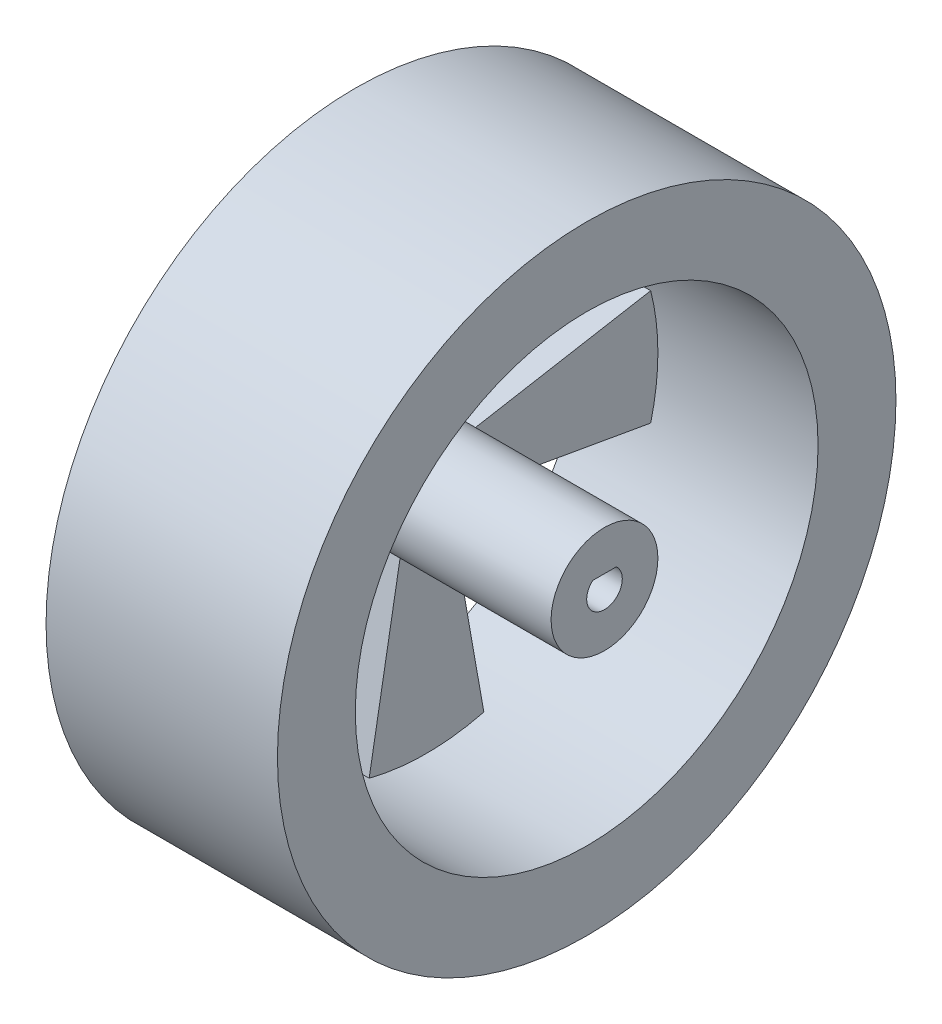
SolidWorks part; units mm, degrees
ref_plane "前视基准面" through (0, 0, 0) normal (0, 0, 1) x (1, 0, 0)
ref_plane "上视基准面" through (0, 0, 0) normal (0, 1, 0) x (1, 0, 0)
ref_plane "右视基准面" through (0, 0, 0) normal (1, 0, 0) x (0, 0, -1)
sketch "草图1" plane through (0, 0, 0) normal (1, 0, 0) x (0, 0, -1)
  circle A0 centre (0, 0) radius 34.75
  circle A1 centre (0, 0) radius 26
  dimension "D1" = 69.5
  dimension "D2" = 52
extrude "凸台-拉伸1" add sketch "草图1" along normal blind 26
ref_plane "基准面1" through (5, 0, 0) normal (1, 0, 0) x (0, 0, -1)
sketch "草图2" plane through (5, 0, 0) normal (1, 0, 0) x (0, 0, -1)
  line L1 (-2.4281, 2.4281) -> (-6.4416, 25.1894)
  line L2 (0, 2) -> (0, 13.4589) construction
  line L3 (2.4281, 2.4281) -> (6.4416, 25.1894)
  line L5 (2.4281, 2.4281) -> (25.1894, 6.4416)
  line L6 (2.4281, -2.4281) -> (25.1894, -6.4416)
  line L7 (2, 0) -> (13.4589, 0) construction
  line L9 (2.4281, -2.4281) -> (6.4416, -25.1894)
  line L10 (-2.4281, -2.4281) -> (-6.4416, -25.1894)
  line L13 (-2.4281, -2.4281) -> (-25.1894, -6.4416)
  line L14 (-2.4281, 2.4281) -> (-25.1894, 6.4416)
  line L16 (0, 0) -> (0, -2) construction
  line L17 (0, 0) -> (-2, 0) construction
  circle A0 centre (0, 0) radius 26 construction
  arc A1 (6.4416, 25.1894) -> (-6.4416, 25.1894) centre (0, 0) ccw
  arc A2 (25.1894, -6.4416) -> (25.1894, 6.4416) centre (0, 0) ccw
  arc A3 (-6.4416, -25.1894) -> (6.4416, -25.1894) centre (0, 0) ccw
  arc A4 (-25.1894, 6.4416) -> (-25.1894, -6.4416) centre (0, 0) ccw
  point P29 (0, 0)
  dimension "D3" = 4
extrude "凸台-拉伸2" add sketch "草图2" along normal blind 3 and the other way blind 3
sketch "草图3" plane through (8, 0, 0) normal (1, 0, 0) x (0, 0, -1)
  circle A0 centre (0, 0) radius 6
  dimension "D1" = 12
extrude "凸台-拉伸3" add sketch "草图3" along normal blind 20
sketch "草图4" plane through (28, 0, 0) normal (1, 0, 0) x (0, 0, -1)
  line L0 (-1.3229, 1.5) -> (1.3229, 1.5)
  arc A0 (-1.3229, 1.5) -> (1.3229, 1.5) centre (0, 0) ccw
  dimension "D2" = 2
  dimension "D1" = 1.5
extrude "切除-拉伸1" cut sketch "草图4" against normal blind 20
